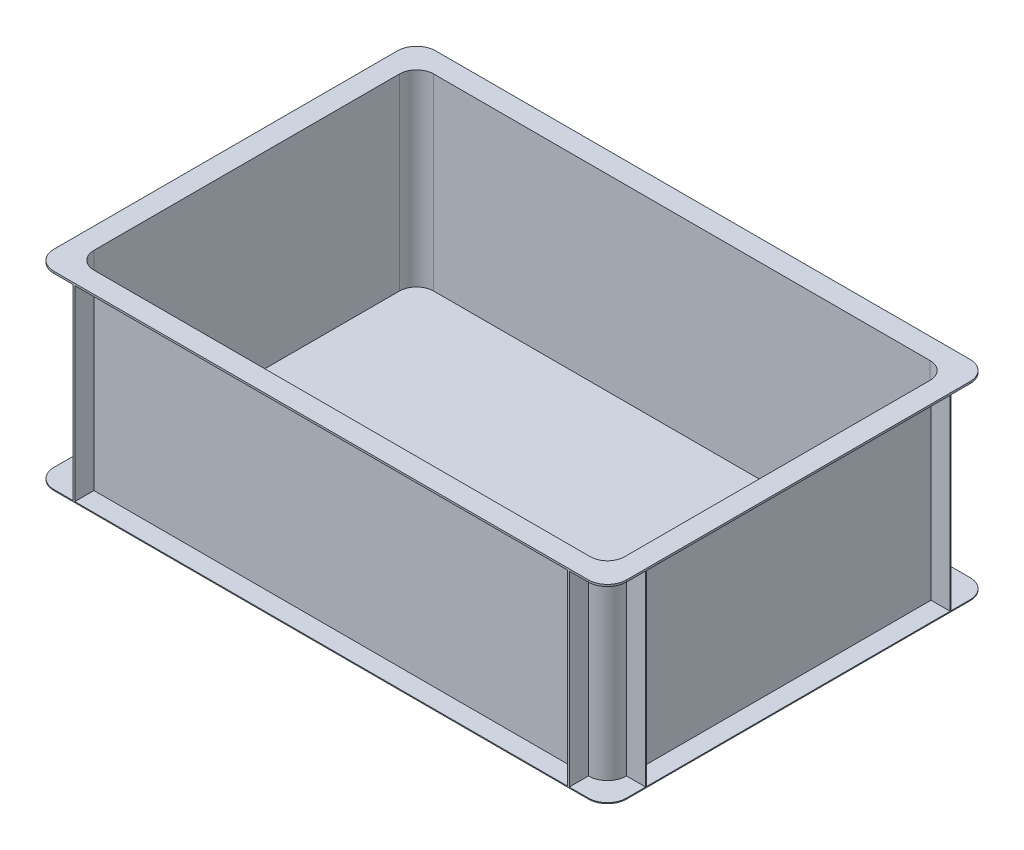
SolidWorks part; units mm, degrees
ref_plane "Front Plane" through (0, 0, 0) normal (0, 0, 1) x (1, 0, 0)
ref_plane "Top Plane" through (0, 0, 0) normal (0, 1, 0) x (1, 0, 0)
ref_plane "Right Plane" through (0, 0, 0) normal (1, 0, 0) x (0, 0, -1)
sketch "Esquisse1" plane through (0, 0, 0) normal (0, 1, 0) x (1, 0, 0)
  line L1 (-280, 200) -> (280, 200)
  line L2 (-300, 180) -> (-300, -180)
  line L3 (-280, -200) -> (280, -200)
  line L4 (300, 180) -> (300, -180)
  line L5 (-300, 200) -> (300, -200) construction
  line L6 (-300, -200) -> (300, 200) construction
  arc A0 (280, -200) -> (300, -180) centre (280, -180) ccw
  arc A1 (280, 200) -> (300, 180) centre (280, 180) cw
  arc A2 (-280, 200) -> (-300, 180) centre (-280, 180) ccw
  arc A3 (-300, -180) -> (-280, -200) centre (-280, -180) ccw
  point P0 (0, 0)
  point P6 (0, 0)
  point P19 (0, 0)
  dimension "D1" = 20
extrude "Boss.-Extru.4" add sketch "Esquisse1" along normal blind 1
sketch "Esquisse3" plane through (0, 1, 0) normal (0, 1, 0) x (1, 0, 0)
  line L0 (-300, 180) -> (-300, -180) construction
  line L1 (-260, 180) -> (260, 180)
  line L2 (-280, 160) -> (-280, -160)
  line L3 (-260, -180) -> (260, -180)
  line L4 (280, 160) -> (280, -160)
  line L5 (-280, 180) -> (280, -180) construction
  line L6 (-280, -180) -> (280, 180) construction
  line L8 (-280, -200) -> (280, -200) construction
  arc A0 (260, -180) -> (280, -160) centre (260, -160) ccw
  arc A1 (260, 180) -> (280, 160) centre (260, 160) cw
  arc A2 (-260, 180) -> (-280, 160) centre (-260, 160) ccw
  arc A3 (-280, -160) -> (-260, -180) centre (-260, -160) ccw
  point P0 (0, 0)
  point P8 (-300, 0)
  point P9 (0, 0)
  dimension "D3" = 20
  dimension "D1" = 20
  dimension "D2" = 20
extrude "Boss.-Extru.5" add sketch "Esquisse3" along normal blind 198
shell "Coque2" thickness 2
ref_plane "Plan1" through (0, 197, 0) normal (0, 1, 0) x (1, 0, 0)
sketch "Esquisse12" plane through (0, 197, 0) normal (0, 1, 0) x (1, 0, 0)
  line L1 (-280, 200) -> (280, 200)
  line L2 (-300, 180) -> (-300, -180)
  line L3 (-280, -200) -> (280, -200)
  line L4 (300, 180) -> (300, -180)
  line L5 (-300, 200) -> (300, -200) construction
  line L6 (-300, -200) -> (300, 200) construction
  arc A0 (280, -200) -> (300, -180) centre (280, -180) ccw
  arc A1 (280, 200) -> (300, 180) centre (280, 180) cw
  arc A2 (-280, 200) -> (-300, 180) centre (-280, 180) ccw
  arc A3 (-300, -180) -> (-280, -200) centre (-280, -180) ccw
  point P0 (0, 0)
  point P5 (0, 0)
  point P6 (0, 0)
  point P7 (0, 0)
  point P20 (0, 0)
  dimension "D1" = 20
extrude "Boss.-Extru.6" add sketch "Esquisse12" along normal blind 2 separate body
sketch "Esquisse17" plane through (0, 199, 0) normal (0, 1, 0) x (1, 0, 0)
  line L1 (-260, 180) -> (260, 180)
  line L2 (-280, 160) -> (-280, -160)
  line L3 (-260, -180) -> (260, -180)
  line L4 (280, 160) -> (280, -160)
  line L5 (-280, 180) -> (280, -180) construction
  line L6 (-280, -180) -> (280, 180) construction
  arc A0 (260, -180) -> (280, -160) centre (260, -160) ccw
  arc A1 (260, 180) -> (280, 160) centre (260, 160) cw
  arc A2 (-260, 180) -> (-280, 160) centre (-260, 160) ccw
  arc A3 (-280, -160) -> (-260, -180) centre (-260, -160) ccw
  point P0 (0, 0)
  point P6 (0, 0)
  point P7 (0, 0)
  point P8 (0, 0)
  dimension "D1" = 20
extrude "Enlèv. mat.-Extru.3" cut sketch "Esquisse17" against normal blind 2
sketch "Esquisse18" plane through (280, 0, 0) normal (1, 0, 0) x (0, 0, -1)
  line L0 (-160, 199) -> (-160, 1) construction
  line L1 (-160, 197) -> (-159, 197)
  line L2 (-160, 197) -> (-160, 1)
  line L3 (-160, 1) -> (-159, 1)
  line L4 (-159, 197) -> (-159, 1)
  line L5 (-180, 1) -> (180, 1) construction
  line L7 (-180, 199) -> (180, 199) construction
  dimension "D1" = 196
  dimension "D2" = 1
  dimension "D3" = 2
extrude "Boss.-Extru.7" add sketch "Esquisse18" along normal blind 20
mirror "Symétrie1" about plane through (0, 0, 0) normal (0, 0, 1) of "Boss.-Extru.4"
ref_plane "Plan3" through (0, 0, 0) normal (0, 0, 1) x (1, 0, 0)
mirror "Symétrie2" about plane through (0, 0, 0) normal (0, 0, 1) of "Boss.-Extru.7"
ref_plane "Plan4" through (0, 0, 0) normal (1, 0, 0) x (0, 0, -1)
mirror "Symétrie3" about plane through (0, 0, 0) normal (1, 0, 0) of "Symétrie2", "Boss.-Extru.7"
sketch "Esquisse19" plane through (0, 0, 180) normal (0, 0, 1) x (1, 0, 0)
  line L1 (-260, 1) -> (-258, 1)
  line L2 (-260, 1) -> (-260, 197)
  line L3 (-260, 197) -> (-258, 197)
  line L4 (-258, 1) -> (-258, 197)
extrude "Boss.-Extru.8" add sketch "Esquisse19" along normal blind 20
mirror "Symétrie4" about plane through (0, 0, 0) normal (1, 0, 0) of "Boss.-Extru.8"
mirror "Symétrie5" about plane through (0, 0, 0) normal (0, 0, 1) of "Symétrie4", "Boss.-Extru.8"
